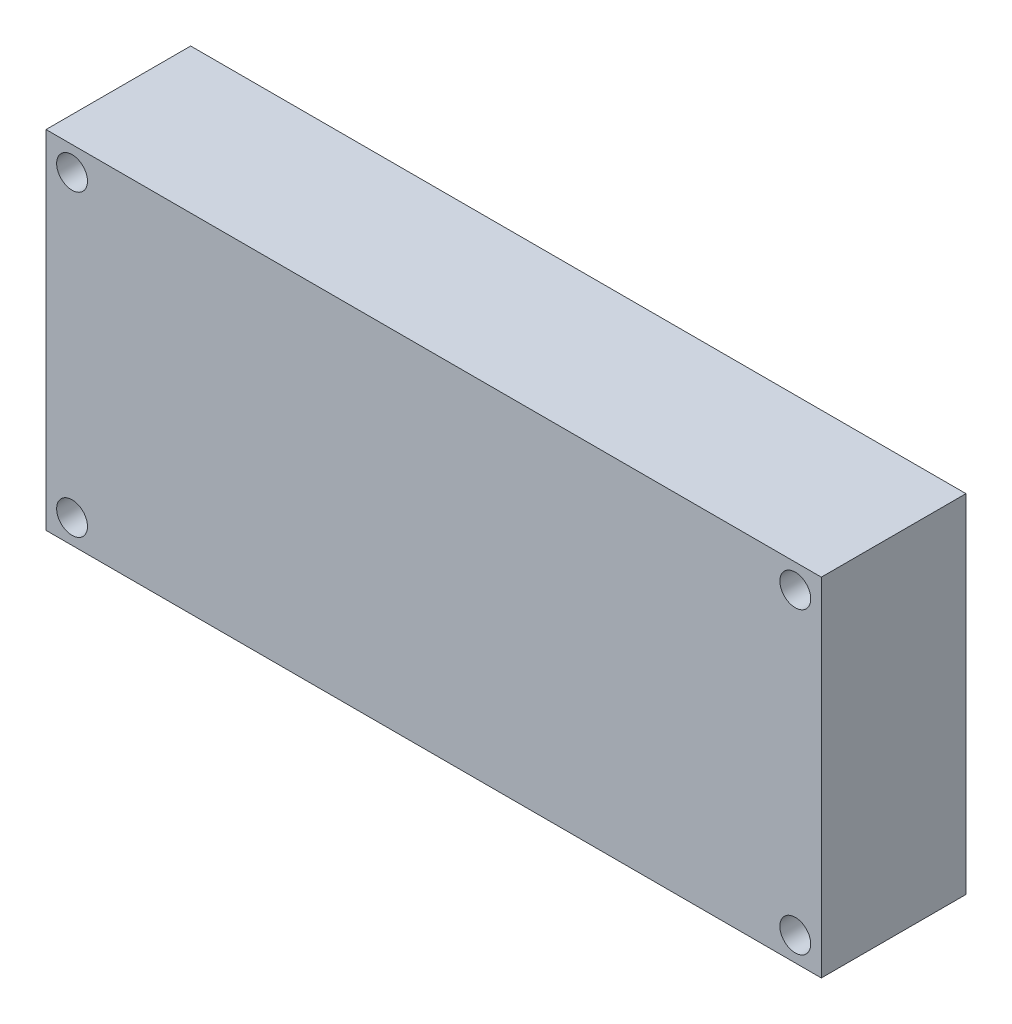
SolidWorks part; units mm, degrees
ref_plane "前基準面" through (0, 0, 0) normal (0, 0, 1) x (1, 0, 0)
ref_plane "上基準面" through (0, 0, 0) normal (0, 1, 0) x (1, 0, 0)
ref_plane "右基準面" through (0, 0, 0) normal (1, 0, 0) x (0, 0, -1)
sketch "草圖1" plane through (0, 0, 0) normal (0, 0, 1) x (1, 0, 0)
  line L1 (-40.2, 18) -> (40.2, 18)
  line L2 (-40.2, 18) -> (-40.2, -18)
  line L3 (-40.2, -18) -> (40.2, -18)
  line L4 (40.2, 18) -> (40.2, -18)
  line L5 (-40.2, 18) -> (40.2, -18) construction
  line L6 (-40.2, -18) -> (40.2, 18) construction
  line L7 (-37.5, 15.5) -> (37.5, 15.5) construction
  line L8 (-37.5, 15.5) -> (-37.5, -15.5) construction
  line L9 (-37.5, -15.5) -> (37.5, -15.5) construction
  line L10 (37.5, 15.5) -> (37.5, -15.5) construction
  line L11 (-37.5, 15.5) -> (37.5, -15.5) construction
  line L12 (-37.5, -15.5) -> (37.5, 15.5) construction
  circle A0 centre (-37.5, 15.5) radius 1.6
  circle A1 centre (-37.5, -15.5) radius 1.6
  circle A2 centre (37.5, -15.5) radius 1.6
  circle A3 centre (37.5, 15.5) radius 1.6
  point P0 (0, 0)
  point P6 (0, 0)
  dimension "D5" = 3.2
  dimension "D1" = 80.4
  dimension "D2" = 36
  dimension "D3" = 31
  dimension "D4" = 75
extrude "伸長1" add sketch "草圖1" along normal blind 15
